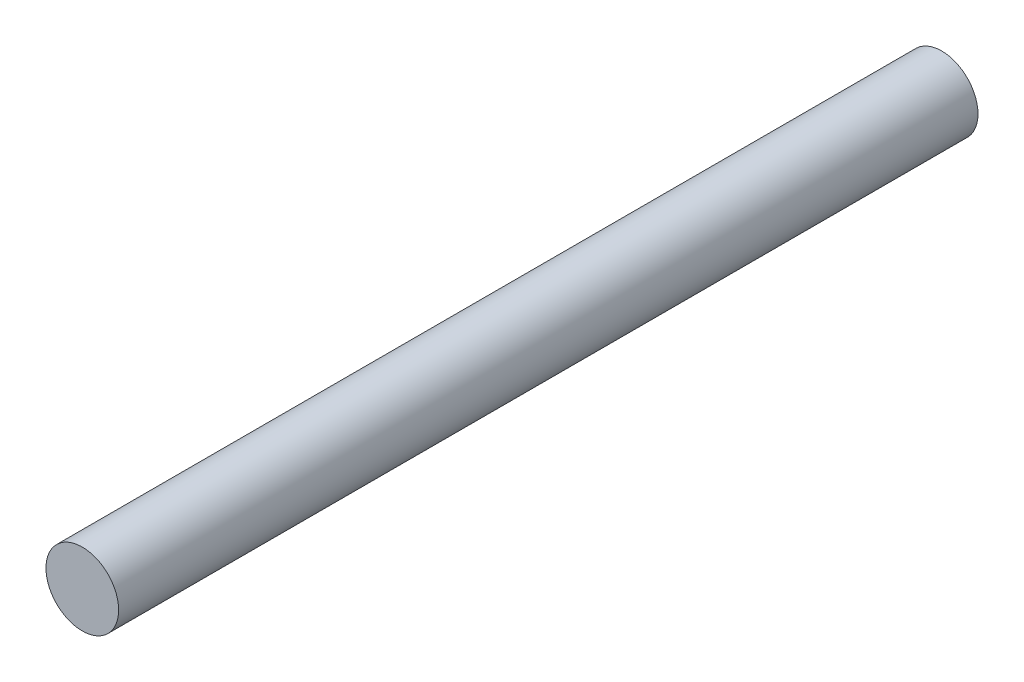
SolidWorks part; units mm, degrees
ref_plane "Front Plane" through (0, 0, 0) normal (0, 0, 1) x (1, 0, 0)
ref_plane "Top Plane" through (0, 0, 0) normal (0, 1, 0) x (1, 0, 0)
ref_plane "Right Plane" through (0, 0, 0) normal (1, 0, 0) x (0, 0, -1)
sketch "Sketch1" plane through (0, 0, 0) normal (0, 0, 1) x (1, 0, 0)
  circle A0 centre (0, 0) radius 11
extrude "HandlePost" add sketch "Sketch1" along normal blind 260
